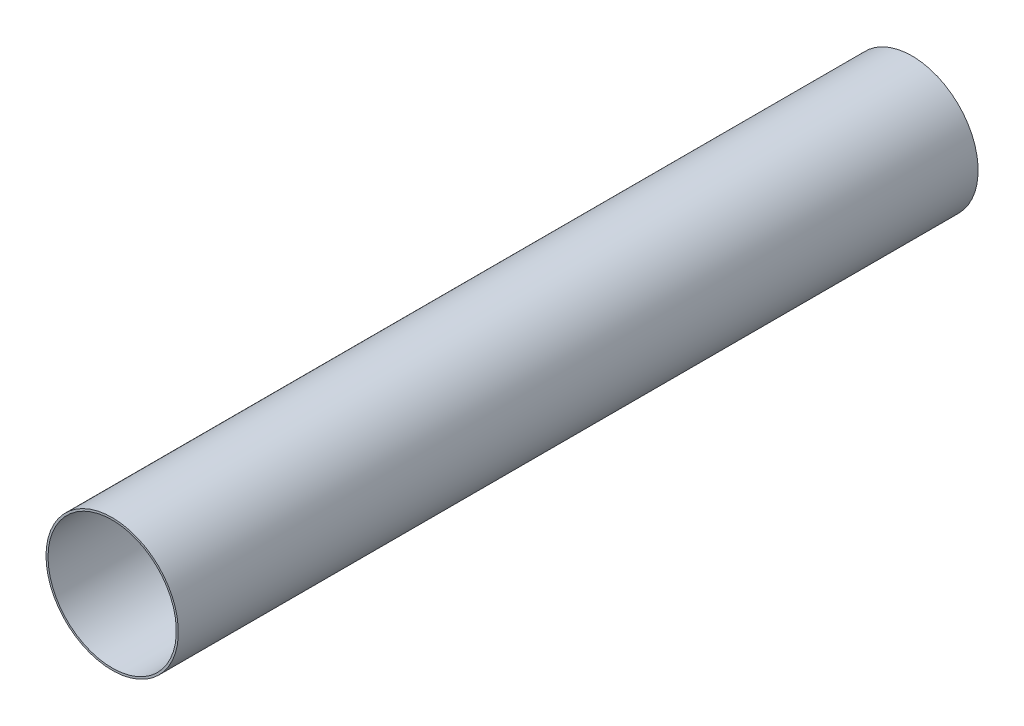
SolidWorks part; units mm, degrees
material "E-Glass Fiber"
ref_plane "Front" through (0, 0, 0) normal (0, 0, 1) x (1, 0, 0)
ref_plane "Top" through (0, 0, 0) normal (0, 1, 0) x (1, 0, 0)
ref_plane "Right" through (0, 0, 0) normal (1, 0, 0) x (0, 0, -1)
sketch "Sketch1" plane through (0, 0, 0) normal (0, 0, 1) x (1, 0, 0)
  circle A0 centre (0, 0) radius 78.6
  circle A1 centre (0, 0) radius 76.2
  dimension "D1" = 157.2
  dimension "D2" = 152.4
extrude "Boss-Extrude1" add sketch "Sketch1" along normal blind 950
